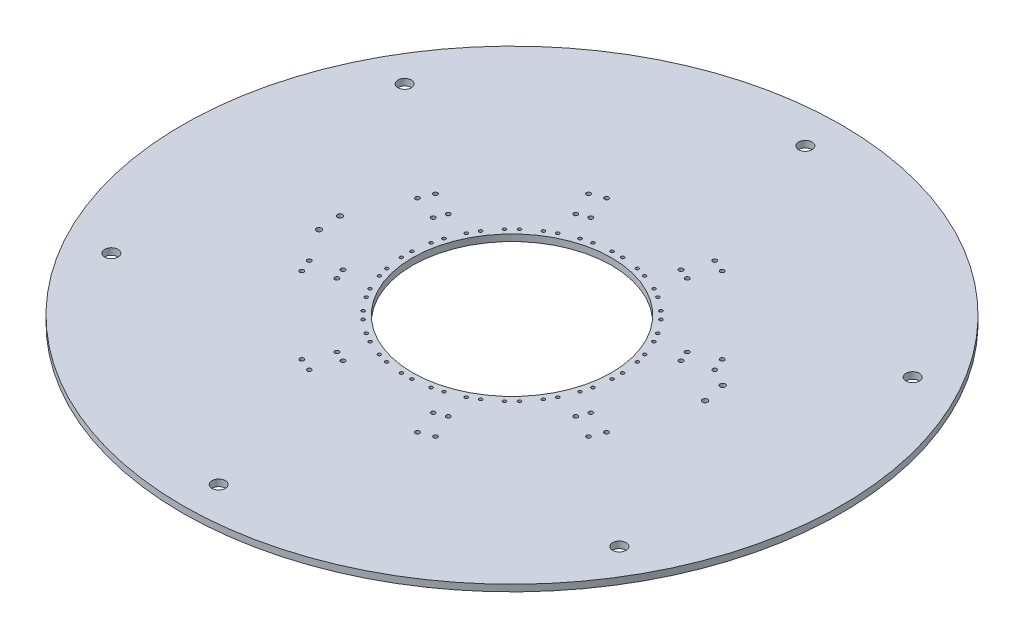
SolidWorks part; units mm, degrees
ref_plane "Front Plane" through (0, 0, 0) normal (0, 0, 1) x (1, 0, 0)
ref_plane "Top Plane" through (0, 0, 0) normal (0, 1, 0) x (1, 0, 0)
ref_plane "Right Plane" through (0, 0, 0) normal (1, 0, 0) x (0, 0, -1)
sketch "Sketch2" plane through (0, 0, 0) normal (0, 1, 0) x (1, 0, 0)
  line L0 (0, 0) -> (0, 231.6511) construction
  line L1 (-26.95, 106.6475) -> (-24.5, 96.9523) construction
  line L2 (26.95, 106.6475) -> (24.5, 96.9523) construction
  line L3 (-25.4301, 105.7349) -> (-23.5925, 98.463) construction
  line L4 (25.4301, 105.7349) -> (23.5925, 98.463) construction
  line L5 (56.7841, 92.7477) -> (52.9415, 86.3062) construction
  line L6 (92.7477, 56.7841) -> (86.3062, 52.9415) construction
  line L7 (105.7349, 25.4301) -> (98.463, 23.5925) construction
  line L8 (105.7349, -25.4301) -> (98.463, -23.5925) construction
  line L9 (92.7477, -56.7841) -> (86.3062, -52.9415) construction
  line L10 (56.7841, -92.7477) -> (52.9415, -86.3062) construction
  line L11 (25.4301, -105.7349) -> (23.5925, -98.463) construction
  line L12 (-25.4301, -105.7349) -> (-23.5925, -98.463) construction
  line L13 (-56.7841, -92.7477) -> (-52.9415, -86.3062) construction
  line L14 (-92.7477, -56.7841) -> (-86.3062, -52.9415) construction
  line L15 (-105.7349, -25.4301) -> (-98.463, -23.5925) construction
  line L16 (-105.7349, 25.4301) -> (-98.463, 23.5925) construction
  line L17 (-92.7477, 56.7841) -> (-86.3062, 52.9415) construction
  line L18 (-56.7841, 92.7477) -> (-52.9415, 86.3062) construction
  line L19 (0, 0) -> (-115.2217, 316.5691) construction
  line L20 (-78.8345, -10.3788) -> (-125.6744, -16.5453) construction
  line L21 (-130.5, 0) -> (0, 0) construction
  line L22 (-129.3836, -17.0337) -> (0, 0) construction
  line L23 (0, 0) -> (2.897, -22.0047) construction
  circle A0 centre (0, 0) radius 250
  circle A1 centre (0, 0) radius 145 construction
  arc A2 (26.95, 106.6475) -> (-26.95, 106.6475) centre (0, 0) ccw construction
  arc A3 (24.5, 96.9523) -> (-24.5, 96.9523) centre (0, 0) ccw construction
  circle A4 centre (0, 0) radius 95 construction
  arc A5 (-24.5, 96.9523) -> (24.5, 96.9523) centre (0, 0) ccw construction
  arc A6 (-26.95, 106.6475) -> (26.95, 106.6475) centre (0, 0) ccw construction
  arc A7 (23.5925, 98.463) -> (-23.5925, 98.463) centre (0, 0) ccw construction
  arc A8 (25.4301, 105.7349) -> (-25.4301, 105.7349) centre (0, 0) ccw construction
  arc A9 (86.3062, 52.9415) -> (52.9415, 86.3062) centre (0, 0) ccw construction
  arc A10 (92.7477, 56.7841) -> (56.7841, 92.7477) centre (0, 0) ccw construction
  arc A11 (98.463, -23.5925) -> (98.463, 23.5925) centre (0, 0) ccw construction
  arc A12 (105.7349, -25.4301) -> (105.7349, 25.4301) centre (0, 0) ccw construction
  arc A13 (52.9415, -86.3062) -> (86.3062, -52.9415) centre (0, 0) ccw construction
  arc A14 (56.7841, -92.7477) -> (92.7477, -56.7841) centre (0, 0) ccw construction
  arc A15 (-23.5925, -98.463) -> (23.5925, -98.463) centre (0, 0) ccw construction
  arc A16 (-25.4301, -105.7349) -> (25.4301, -105.7349) centre (0, 0) ccw construction
  arc A17 (-86.3062, -52.9415) -> (-52.9415, -86.3062) centre (0, 0) ccw construction
  arc A18 (-92.7477, -56.7841) -> (-56.7841, -92.7477) centre (0, 0) ccw construction
  arc A19 (-98.463, 23.5925) -> (-98.463, -23.5925) centre (0, 0) ccw construction
  arc A20 (-105.7349, 25.4301) -> (-105.7349, -25.4301) centre (0, 0) ccw construction
  arc A21 (-52.9415, 86.3062) -> (-86.3062, 52.9415) centre (0, 0) ccw construction
  arc A22 (-56.7841, 92.7477) -> (-92.7477, 56.7841) centre (0, 0) ccw construction
  circle A23 centre (0, 222.5) radius 5.1
  circle A31 centre (0, 0) radius 75.5
  circle A32 centre (0, 80) radius 2.5 construction
  circle A33 centre (0, 40) radius 2.5 construction
  circle A34 centre (28.2843, 28.2843) radius 2.5 construction
  circle A35 centre (56.5685, 56.5685) radius 2.5 construction
  circle A36 centre (40, 0) radius 2.5 construction
  circle A37 centre (80, 0) radius 2.5 construction
  circle A38 centre (28.2843, -28.2843) radius 2.5 construction
  circle A39 centre (56.5685, -56.5685) radius 2.5 construction
  circle A40 centre (0, -40) radius 2.5 construction
  circle A41 centre (0, -80) radius 2.5 construction
  circle A42 centre (-28.2843, -28.2843) radius 2.5 construction
  circle A43 centre (-56.5685, -56.5685) radius 2.5 construction
  circle A44 centre (-40, 0) radius 2.5 construction
  circle A45 centre (-80, 0) radius 2.5 construction
  circle A46 centre (-28.2843, 28.2843) radius 2.5 construction
  circle A47 centre (-56.5685, 56.5685) radius 2.5 construction
  circle A48 centre (0, 0) radius 80 construction
  circle A49 centre (0, 80) radius 1.5 construction
  circle A50 centre (4, 79.8999) radius 1.25
  circle A51 centre (-4, 79.8999) radius 1.25
  circle A52 centre (16.8159, 78.2127) radius 1.25
  circle A53 centre (24.5433, 76.1421) radius 1.25
  circle A54 centre (36.4859, 71.1954) radius 1.25
  circle A55 centre (43.4141, 67.1954) radius 1.25
  circle A56 centre (53.6694, 59.3262) radius 1.25
  circle A57 centre (59.3262, 53.6694) radius 1.25
  circle A58 centre (67.1954, 43.4141) radius 1.25
  circle A59 centre (71.1954, 36.4859) radius 1.25
  circle A60 centre (76.1421, 24.5433) radius 1.25
  circle A61 centre (78.2127, 16.8159) radius 1.25
  circle A62 centre (79.8999, 4) radius 1.25
  circle A63 centre (79.8999, -4) radius 1.25
  circle A64 centre (78.2127, -16.8159) radius 1.25
  circle A65 centre (76.1421, -24.5433) radius 1.25
  circle A66 centre (-157.3313, 157.3313) radius 5.1 [skipped]
  circle A67 centre (-222.5, 0) radius 5.1 [skipped]
  circle A68 centre (-157.3313, -157.3313) radius 5.1 [skipped]
  circle A69 centre (0, -222.5) radius 5.1 [skipped]
  circle A70 centre (157.3313, -157.3313) radius 5.1 [skipped]
  circle A71 centre (222.5, 0) radius 5.1 [skipped]
  circle A72 centre (157.3313, 157.3313) radius 5.1 [skipped]
  circle A73 centre (192.6907, 111.25) radius 5.1
  circle A74 centre (192.6907, -111.25) radius 5.1
  circle A75 centre (0, -222.5) radius 5.1
  circle A76 centre (-192.6907, -111.25) radius 5.1
  circle A77 centre (-192.6907, 111.25) radius 5.1
  circle A78 centre (-41.0424, 112.7631) radius 1.6
  circle A79 centre (0, 0) radius 120 construction
  circle A80 centre (0, 0) radius 100 construction
  circle A81 centre (-34.202, 93.9693) radius 1.6
  circle A82 centre (41.0424, 112.7631) radius 1.6
  circle A83 centre (34.202, 93.9693) radius 1.6
  circle A84 centre (90.6308, 42.2618) radius 1.6
  circle A85 centre (42.2618, 90.6308) radius 1.6
  circle A86 centre (50.7142, 108.7569) radius 1.6
  circle A87 centre (108.7569, 50.7142) radius 1.6
  circle A88 centre (93.9693, -34.202) radius 1.6
  circle A89 centre (93.9693, 34.202) radius 1.6
  circle A90 centre (112.7631, 41.0424) radius 1.6
  circle A91 centre (112.7631, -41.0424) radius 1.6
  circle A92 centre (42.2618, -90.6308) radius 1.6
  circle A93 centre (90.6308, -42.2618) radius 1.6
  circle A94 centre (108.7569, -50.7142) radius 1.6
  circle A95 centre (50.7142, -108.7569) radius 1.6
  circle A96 centre (-34.202, -93.9693) radius 1.6
  circle A97 centre (34.202, -93.9693) radius 1.6
  circle A98 centre (41.0424, -112.7631) radius 1.6
  circle A99 centre (-41.0424, -112.7631) radius 1.6
  circle A100 centre (-90.6308, -42.2618) radius 1.6
  circle A101 centre (-42.2618, -90.6308) radius 1.6
  circle A102 centre (-50.7142, -108.7569) radius 1.6
  circle A103 centre (-108.7569, -50.7142) radius 1.6
  circle A104 centre (-93.9693, 34.202) radius 1.6
  circle A105 centre (-93.9693, -34.202) radius 1.6
  circle A106 centre (-112.7631, -41.0424) radius 1.6
  circle A107 centre (-112.7631, 41.0424) radius 1.6
  circle A108 centre (-42.2618, 90.6308) radius 1.6
  circle A109 centre (-90.6308, 42.2618) radius 1.6
  circle A110 centre (-108.7569, 50.7142) radius 1.6
  circle A111 centre (-50.7142, 108.7569) radius 1.6
  circle A112 centre (71.1954, -36.4859) radius 1.25
  circle A113 centre (67.1954, -43.4141) radius 1.25
  circle A114 centre (59.3262, -53.6694) radius 1.25
  circle A115 centre (53.6694, -59.3262) radius 1.25
  circle A116 centre (43.4141, -67.1954) radius 1.25
  circle A117 centre (36.4859, -71.1954) radius 1.25
  circle A118 centre (24.5433, -76.1421) radius 1.25
  circle A119 centre (16.8159, -78.2127) radius 1.25
  circle A120 centre (4, -79.8999) radius 1.25
  circle A121 centre (-4, -79.8999) radius 1.25
  circle A122 centre (-16.8159, -78.2127) radius 1.25
  circle A123 centre (-24.5433, -76.1421) radius 1.25
  circle A124 centre (-36.4859, -71.1954) radius 1.25
  circle A125 centre (-43.4141, -67.1954) radius 1.25
  circle A126 centre (-53.6694, -59.3262) radius 1.25
  circle A127 centre (-59.3262, -53.6694) radius 1.25
  circle A128 centre (-67.1954, -43.4141) radius 1.25
  circle A129 centre (-71.1954, -36.4859) radius 1.25
  circle A130 centre (-76.1421, -24.5433) radius 1.25
  circle A131 centre (-78.2127, -16.8159) radius 1.25
  circle A132 centre (-79.8999, -4) radius 1.25
  circle A133 centre (-79.8999, 4) radius 1.25
  circle A134 centre (-78.2127, 16.8159) radius 1.25
  circle A135 centre (-76.1421, 24.5433) radius 1.25
  circle A136 centre (-71.1954, 36.4859) radius 1.25
  circle A137 centre (-67.1954, 43.4141) radius 1.25
  circle A138 centre (-59.3262, 53.6694) radius 1.25
  circle A139 centre (-53.6694, 59.3262) radius 1.25
  circle A140 centre (-43.4141, 67.1954) radius 1.25
  circle A141 centre (-36.4859, 71.1954) radius 1.25
  circle A142 centre (-24.5433, 76.1421) radius 1.25
  circle A143 centre (-16.8159, 78.2127) radius 1.25
  circle A144 centre (-129.3836, -17.0337) radius 2
  circle A145 centre (-130.5, 0) radius 2
  circle A146 centre (129.3836, 17.0337) radius 2
  circle A147 centre (126.0533, 33.7759) radius 2
  point P46 (0, 0)
  point P63 (0, 0)
  point P132 (0, 0)
  point P211 (0, 0)
  dimension "D1" = 500
  dimension "D2" = 290
  dimension "D3" = 220
  dimension "D4" = 200
  dimension "D5" = 190
  dimension "D9" = 10.2
  dimension "D11" = 151
  dimension "D12" = 40
  dimension "D14" = 5
  dimension "D15" = 160
  dimension "D16" = 3
  dimension "D17" = 4
  dimension "D18" = 2.5
  dimension "D21" = 240
  dimension "D22" = 200
  dimension "D24" = 3.2
  dimension "D26" = 4
  dimension "D27" = 4
  dimension "D6" = 49
  dimension "D7" = 1.25
  dimension "D10" = 222.5
  dimension "D13" = 40
  dimension "D23" = 20
  dimension "D28" = 130.5
  dimension "D29" = 130.5
  dimension "D30" = 7.5
  dimension "D8" = 8
  dimension "D19" = 24
  dimension "D20" = 6
  dimension "D25" = 8
extrude "Boss-Extrude1" add sketch "Sketch2" along normal mid plane 5
